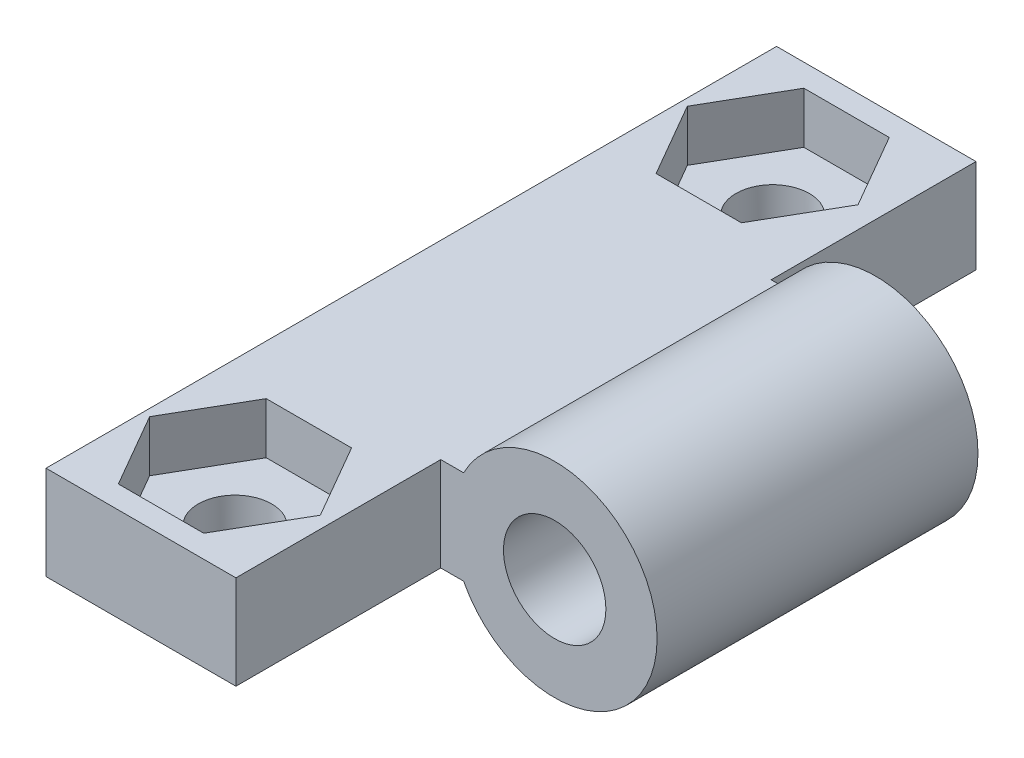
SolidWorks part; units mm, degrees
ref_plane "前视基准面" through (0, 0, 0) normal (0, 0, 1) x (1, 0, 0)
ref_plane "上视基准面" through (0, 0, 0) normal (0, 1, 0) x (1, 0, 0)
ref_plane "右视基准面" through (0, 0, 0) normal (1, 0, 0) x (0, 0, -1)
sketch "草图1" plane through (0, 0, 0) normal (0, 1, 0) x (1, 0, 0)
  line L1 (0, 0) -> (17.8, 0)
  line L2 (0, 0) -> (0, -42.8)
  line L3 (0, -42.8) -> (17.8, -42.8)
  line L4 (17.8, 0) -> (17.8, -42.8)
  dimension "D1" = 42.8
  dimension "D2" = 17.8
extrude "凸台-拉伸1" add sketch "草图1" along normal blind 5.5
sketch "草图6" plane through (0, 5.5, 0) normal (0, 1, 0) x (1, 0, 0)
  line L0 (0, -42.8) -> (17.8, -42.8) construction
  circle A0 centre (5.4204, -5.65) radius 2.15
  circle A1 centre (5.4204, -37.15) radius 2.15
  dimension "D1" = 4.3
  dimension "D2" = 31.5
  dimension "D3" = 5.65
extrude "切除-拉伸3" cut sketch "草图6" against normal blind 10
sketch "草图7" plane through (0, 5.5, 0) normal (0, 1, 0) x (1, 0, 0)
  line L16 (2.9204, -1.3199) -> (7.9204, -1.3199)
  line L17 (7.9204, -1.3199) -> (10.4204, -5.65)
  line L18 (10.4204, -5.65) -> (7.9204, -9.9801)
  line L19 (7.9204, -9.9801) -> (2.9204, -9.9801)
  line L20 (2.9204, -9.9801) -> (0.4204, -5.65)
  line L21 (0.4204, -5.65) -> (2.9204, -1.3199)
  line L22 (7.9204, -1.3199) -> (2.9204, -9.9801) construction
  line L23 (2.9204, -1.3199) -> (7.9204, -9.9801) construction
  line L24 (0.4204, -5.65) -> (10.4204, -5.65) construction
  line L25 (0.4204, -37.15) -> (2.9204, -32.8199)
  line L26 (2.9204, -32.8199) -> (7.9204, -32.8199)
  line L27 (7.9204, -32.8199) -> (10.4204, -37.15)
  line L28 (10.4204, -37.15) -> (7.9204, -41.4801)
  line L29 (7.9204, -41.4801) -> (2.9204, -41.4801)
  line L30 (2.9204, -41.4801) -> (0.4204, -37.15)
  circle A1 centre (5.4204, -5.65) radius 2.15 construction
  dimension "D2" = 5
  dimension "D3" = 5
  dimension "D1" = 5
  dimension "D4" = 2
extrude "切除-拉伸4" cut sketch "草图7" against normal blind 3
ref_plane "基准面1" through (0, 0, 12) normal (0, 0, -1) x (-1, 0, 0)
ref_plane "基准面3" through (0, 0, 30.8) normal (0, 0, 1) x (1, 0, 0)
sketch "草图10" plane through (0, 0, 30.8) normal (0, 0, 1) x (1, 0, 0)
  line L0 (17.8, 5.5) -> (17.8, 0) construction
  circle A0 centre (17.8, 2.75) radius 6
extrude "凸台-拉伸5" add sketch "草图10" against normal up to surface (18.8 mm away) up to plane "基准面1"
sketch "草图12" plane through (0, 0, 42.8) normal (0, 0, 1) x (1, 0, 0)
  line L1 (11.1256, 9.8569) -> (20.4241, 9.8569)
  line L2 (11.1256, 9.8569) -> (11.1256, -4.3822)
  line L3 (11.1256, -4.3822) -> (20.4241, -4.3822)
  line L4 (20.4241, 9.8569) -> (20.4241, -4.3822)
extrude "切除-拉伸5" cut sketch "草图12" against normal up to surface (12 mm away) up to face at (17.9668, 2.75, 30.8)
sketch "草图13" plane through (0, 0, 0) normal (0, 0, -1) x (-1, 0, 0)
  line L1 (-11.683, 11.3517) -> (-19.9934, 11.3517)
  line L2 (-11.683, 11.3517) -> (-11.683, -4.3315)
  line L3 (-11.683, -4.3315) -> (-19.9934, -4.3315)
  line L4 (-19.9934, 11.3517) -> (-19.9934, -4.3315)
  point P4 (-11.683, -4.3315)
extrude "切除-拉伸6" cut sketch "草图13" against normal up to surface (12 mm away) up to face at (17.9668, 2.75, 12)
sketch "草图14" plane through (0, 0, 30.8) normal (0, 0, 1) x (1, 0, 0)
  circle A0 centre (17.8, 2.75) radius 3
  arc A1 (12.4673, 0) -> (12.4673, 5.5) centre (17.8, 2.75) ccw construction
  dimension "D1" = 0
extrude "切除-拉伸7" cut sketch "草图14" against normal blind 22
